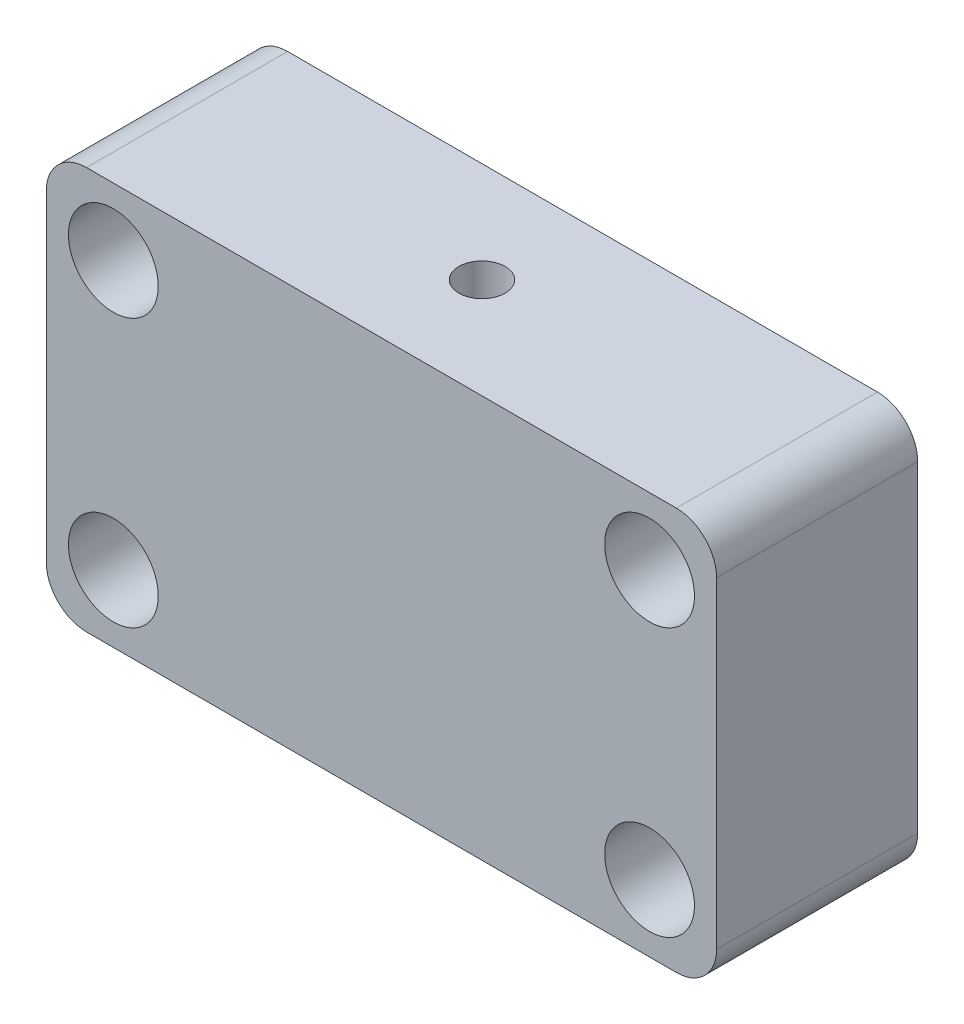
SolidWorks part; units mm, degrees
ref_plane "Front Plane" through (0, 0, 0) normal (0, 0, 1) x (1, 0, 0)
ref_plane "Top Plane" through (0, 0, 0) normal (0, 1, 0) x (1, 0, 0)
ref_plane "Right Plane" through (0, 0, 0) normal (1, 0, 0) x (0, 0, -1)
sketch "Sketch2" plane through (0, 0, 0) normal (0, 0, 1) x (1, 0, 0)
  line L1 (-25, -15) -> (25, -15)
  line L2 (-25, -15) -> (-25, 15)
  line L3 (-25, 15) -> (25, 15)
  line L4 (25, -15) -> (25, 15)
  line L5 (-25, -15) -> (25, 15) construction
  line L6 (-25, 15) -> (25, -15) construction
  circle A0 centre (20, 10) radius 3.35
  circle A1 centre (-20, 10) radius 3.35
  circle A2 centre (-20, -10) radius 3.35
  circle A3 centre (20, -10) radius 3.35
  point P0 (0, 0)
  dimension "D3" = 20
  dimension "D1" = 30
  dimension "D2" = 50
  dimension "D4" = 10
extrude "Boss-Extrude1" add sketch "Sketch2" along normal blind 15
sketch "Sketch7" plane through (0, 15, 0) normal (0, 1, 0) x (1, 0, 0)
  line L0 (0, 0) -> (0, -15) construction
  line L1 (25, 0) -> (-25, 0) construction
  line L2 (25, -15) -> (-25, -15) construction
  point P6 (0, -7.5)
sketch "Sketch8" plane through (0, 0, 0) normal (0, 0, -1) x (-1, 0, 0)
  line L0 (25, -15) -> (-25, 15) construction
  line L1 (25, 15) -> (-25, -15) construction
  point P4 (0, 0)
  point P8 (0, 0)
hole_wizard "#8-32 Tapped Hole1" positions "3DSketch1" profile "Sketch9" tap size "#8-32" standard "ANSI Inch"
sketch3d "3DSketch1"
  point P0 (0, 15, 7.5)
sketch "Sketch9" plane through (0, 15, 7.5) normal (1, 0, 0) x (0, 0, 1)
  line L0 (0, 0) -> (0, 6.0378)
  line L1 (0, 6.0378) -> (1.7272, 5)
  line L2 (1.7272, 5) -> (1.7272, 0)
  line L5 (1.7272, 0) -> (0, 0)
  line L10 (0, 6.0378) -> (-1.7272, 5) construction
  line L11 (0, -6.35) -> (0, 107.95) construction
  dimension "Tap Drill Dia." = 3.4544
  dimension "Tap Drill Depth" = 5
  dimension "Drill Angle" = 118
fillet "Fillet1" radius 3 1 edges at (25, 15, 7.5)
fillet "Fillet2" radius 3 1 edges at (-25, 15, 7.5)
fillet "Fillet3" radius 3 1 edges at (25, -15, 7.5)
fillet "Fillet4" radius 3 1 edges at (-25, -15, 7.5)
